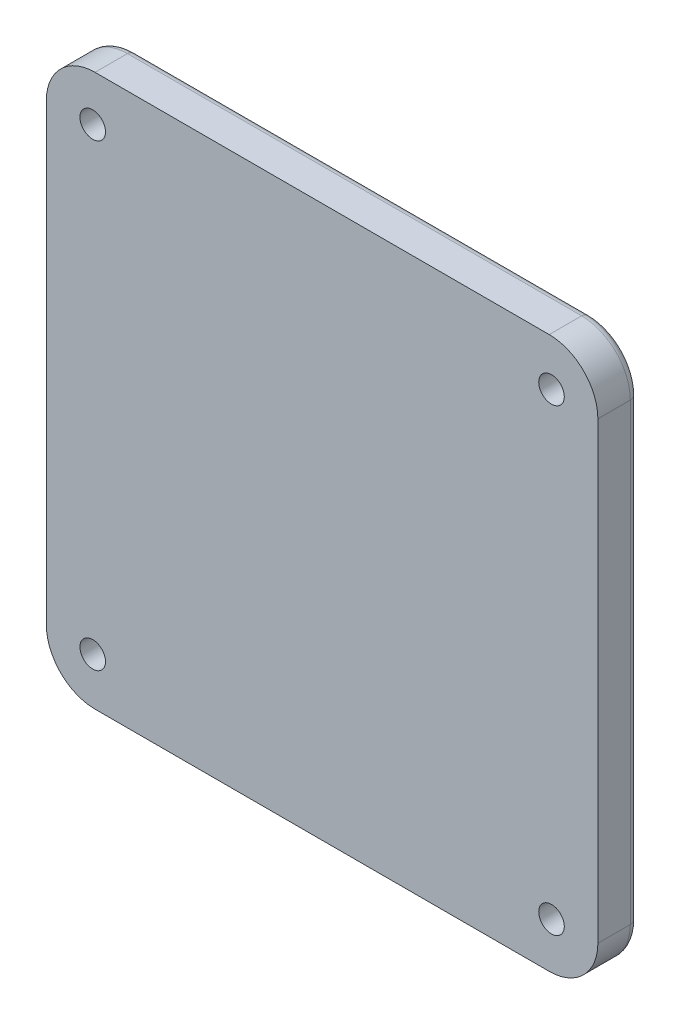
SolidWorks part; units mm, degrees
ref_plane "Front Plane" through (0, 0, 0) normal (0, 0, 1) x (1, 0, 0)
ref_plane "Top Plane" through (0, 0, 0) normal (0, 1, 0) x (1, 0, 0)
ref_plane "Right Plane" through (0, 0, 0) normal (1, 0, 0) x (0, 0, -1)
sketch "Sketch1" plane through (0, 0, -97.5071) normal (0, 0, -1) x (-1, 0, 0)
  line L1 (-61.0728, 13.2587) -> (-117.0728, 13.2587)
  line L2 (-55.0728, 19.2587) -> (-55.0728, 75.2587)
  line L3 (-61.0728, 81.2587) -> (-117.0728, 81.2587)
  line L4 (-123.0728, 19.2587) -> (-123.0728, 75.2587)
  line L5 (-55.0728, 13.2587) -> (-123.0728, 81.2587) construction
  line L6 (-55.0728, 81.2587) -> (-123.0728, 13.2587) construction
  arc A0 (-117.0728, 13.2587) -> (-123.0728, 19.2587) centre (-117.0728, 19.2587) cw
  arc A1 (-61.0728, 13.2587) -> (-55.0728, 19.2587) centre (-61.0728, 19.2587) ccw
  arc A2 (-55.0728, 75.2587) -> (-61.0728, 81.2587) centre (-61.0728, 75.2587) ccw
  arc A3 (-117.0728, 81.2587) -> (-123.0728, 75.2587) centre (-117.0728, 75.2587) ccw
  circle A4 centre (-117.3571, 75.543) radius 1.575
  circle A5 centre (-60.7885, 75.543) radius 1.575
  circle A6 centre (-60.7885, 18.9744) radius 1.575
  circle A7 centre (-117.3571, 18.9744) radius 1.575
  point P0 (-89.0728, 47.2587)
  point P30 (-89.0728, 47.2587)
  dimension "D3" = 6
  dimension "D4" = 3.15
  dimension "D1" = 68
  dimension "D2" = 68
  dimension "D5" = 4
extrude "Boss-Extrude1" add sketch "Sketch1" along normal blind 5
fillet "Fillet1" radius 1 8 edges at (121.3154, 79.5013, -102.5071) (89.0728, 81.2587, -102.5071) (56.8302, 79.5013, -102.5071) (55.0728, 47.2587, -102.5071) (56.8302, 15.0161, -102.5071) (89.0728, 13.2587, -102.5071) (121.3154, 15.0161, -102.5071) (123.0728, 47.2587, -102.5071)
